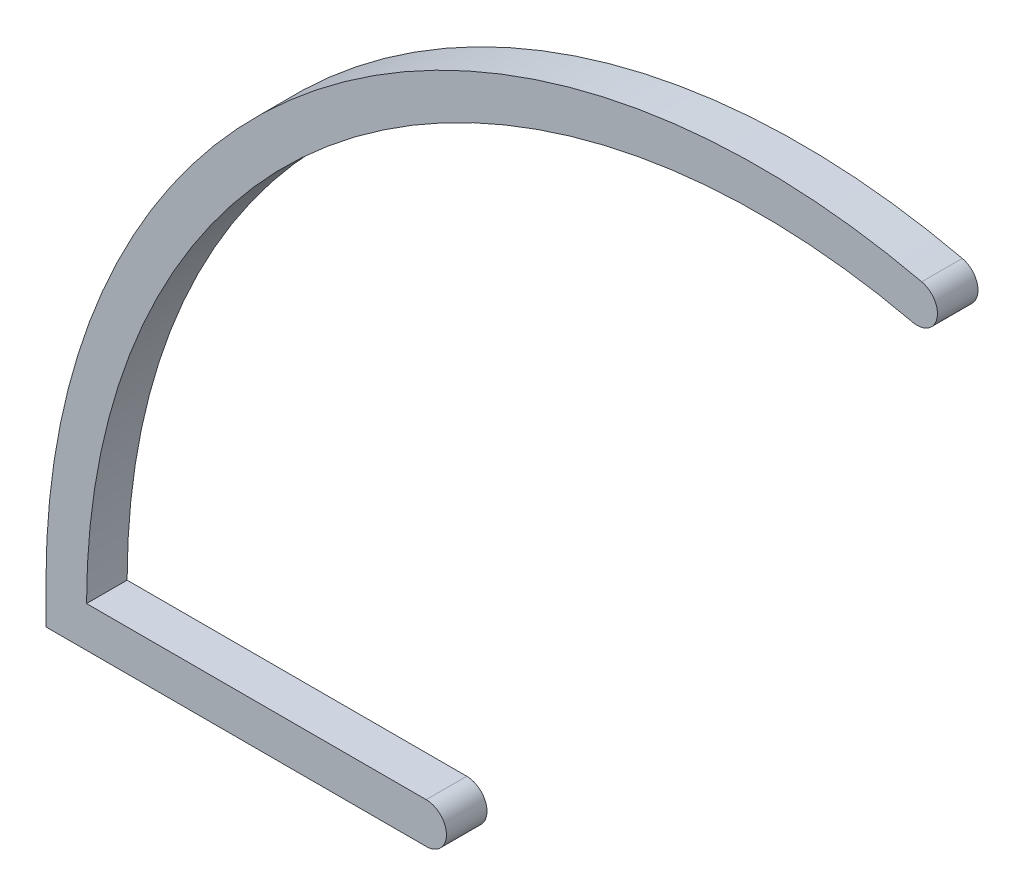
SolidWorks part; units mm, degrees
ref_plane "Front Plane" through (0, 0, 0) normal (0, 0, 1) x (1, 0, 0)
ref_plane "Top Plane" through (0, 0, 0) normal (0, 1, 0) x (1, 0, 0)
ref_plane "Right Plane" through (0, 0, 0) normal (1, 0, 0) x (0, 0, -1)
sketch "Sketch1" plane through (0, 0, 0) normal (0, 0, 1) x (1, 0, 0)
  line L1 (552.8215, 848.9611) -> (459.0883, 848.9611)
  line L3 (552.8215, 858.9611) -> (469.0883, 858.9611)
  line L4 (459.0883, 848.9611) -> (459.0883, 858.9611)
  arc A0 (552.8215, 848.9611) -> (552.8215, 858.9611) centre (552.8215, 853.9611) ccw
  arc A1 (459.0883, 858.9611) -> (675.009, 1030.6275) centre (635.2898, 858.9611) cw
  arc A2 (675.009, 1030.6275) -> (672.7548, 1020.8849) centre (673.8819, 1025.7562) cw
  arc A3 (672.7548, 1020.8849) -> (469.0883, 858.9611) centre (635.2898, 858.9611) ccw
  point P9 (552.8215, 909.2082)
  point P11 (0, 0)
  point P12 (459.0883, 848.9611)
  point P14 (498.0617, 893.8062)
  point P15 (652.1988, 980.0554)
  point P16 (552.8215, 846.7103)
  dimension "D1" = 10
  dimension "D2" = 5
extrude "Boss-Extrude1" add sketch "Sketch1" along normal mid plane 10
ref_point "Point1"
